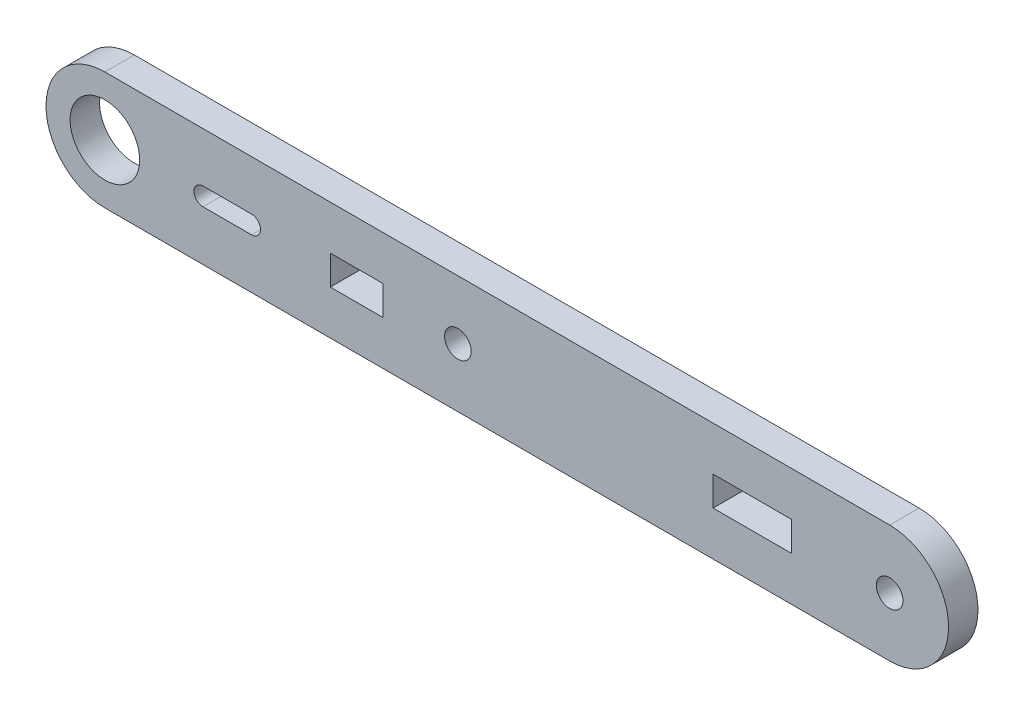
SolidWorks part; units mm, degrees
ref_plane "前视基准面" through (0, 0, 0) normal (0, 0, 1) x (1, 0, 0)
ref_plane "上视基准面" through (0, 0, 0) normal (0, 1, 0) x (1, 0, 0)
ref_plane "右视基准面" through (0, 0, 0) normal (1, 0, 0) x (0, 0, -1)
ref_plane "基准面1" through (0, 0, 3) normal (0, 0, 1) x (1, 0, 0)
sketch "草图1" plane through (0, 0, 3) normal (0, 0, 1) x (1, 0, 0)
  line L0 (-26.3778, 4.4994) -> (-26.3778, 7.4995)
  line L1 (-26.3778, 7.4995) -> (-21.005, 7.4995)
  line L2 (-21.005, 7.4995) -> (-21.005, 4.4994)
  line L3 (-21.005, 4.4994) -> (-26.3778, 4.4994)
  line L4 (-39.3523, 6.9343) -> (-34.4047, 6.9343)
  line L5 (-34.4047, 5.1001) -> (-39.3523, 5.1001)
  line L6 (-49.3435, 0) -> (30.6182, 0)
  line L7 (30.6182, 12) -> (-49.3435, 12)
  line L8 (20.6213, 4.4994) -> (12.6221, 4.4994)
  line L9 (12.6221, 4.4994) -> (12.6221, 7.4995)
  line L10 (12.6221, 7.4995) -> (20.6213, 7.4995)
  line L11 (20.6213, 7.4995) -> (20.6213, 4.4994)
  arc A0 (-39.3523, 5.1001) -> (-39.3523, 6.9343) centre (-39.3523, 6.0172) cw
  arc A1 (-34.4047, 6.9343) -> (-34.4047, 5.1001) centre (-34.4047, 6.0172) cw
  circle A2 centre (-49.3435, 6) radius 3.5438
  circle A3 centre (-13.3753, 6.0002) radius 1.3576
  circle A4 centre (30.6116, 6.0001) radius 1.3576
  arc A5 (30.6182, 0) -> (30.6182, 12) centre (30.6182, 6) ccw
  arc A6 (-49.3435, 12) -> (-49.3435, 0) centre (-49.3435, 6) ccw
extrude "凸台-拉伸1" add sketch "草图1" against normal blind 3
